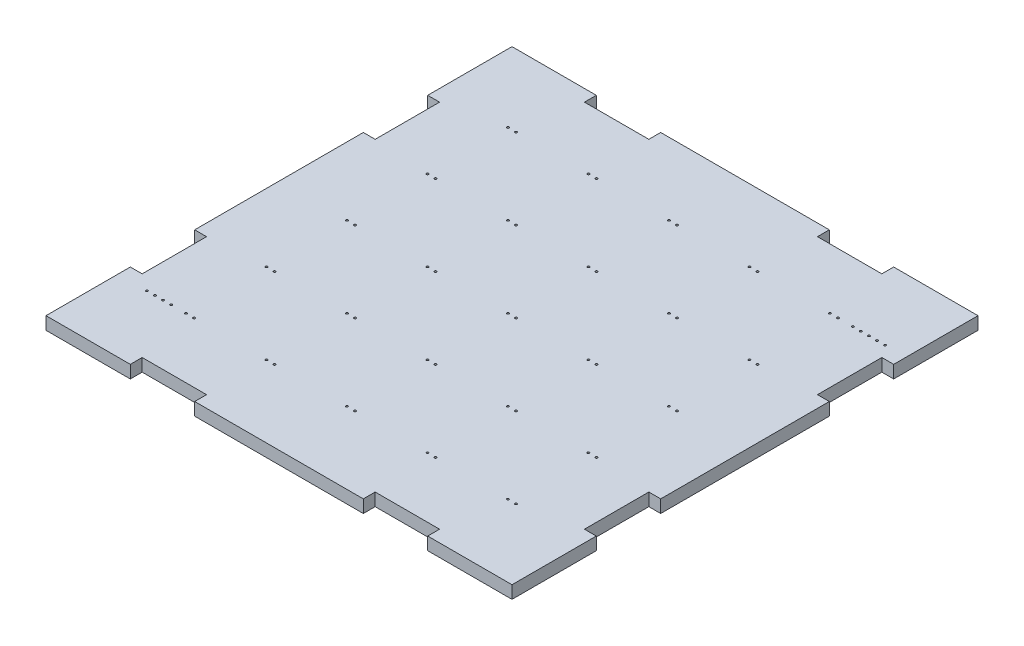
SolidWorks part; units mm, degrees
ref_plane "Front Plane" through (0, 0, 0) normal (0, 0, 1) x (1, 0, 0)
ref_plane "Top Plane" through (0, 0, 0) normal (0, 1, 0) x (1, 0, 0)
ref_plane "Right Plane" through (0, 0, 0) normal (1, 0, 0) x (0, 0, -1)
sketch "Sketch2" plane through (0, 0, 0) normal (0, 1, 0) x (1, 0, 0)
  line L1 (-110, -110) -> (110, -110)
  line L2 (-110, -110) -> (-110, 110)
  line L3 (-110, 110) -> (110, 110)
  line L4 (110, -110) -> (110, 110)
  line L5 (-110, -110) -> (110, 110) construction
  line L6 (-110, 110) -> (110, -110) construction
  point P0 (0, 0)
  dimension "D1" = 220
  dimension "D2" = 220
extrude "Boss-Extrude1" add sketch "Sketch2" along normal blind 6
sketch "Sketch3" plane through (0, 6, 0) normal (0, 1, 0) x (1, 0, 0)
  line L0 (-110, 110) -> (-110, -110) construction
  line L2 (-110, -110) -> (110, -110) construction
  circle A0 centre (-77.905, -76) radius 0.5
  circle A1 centre (-74.095, -76) radius 0.5
  circle A2 centre (-76, -76) radius 4 construction
  circle A3 centre (-38, -76) radius 4 construction
  circle A4 centre (-39.905, -76) radius 0.5
  circle A5 centre (-36.095, -76) radius 0.5
  circle A6 centre (0, -76) radius 4 construction
  circle A7 centre (-1.905, -76) radius 0.5
  circle A8 centre (1.905, -76) radius 0.5
  circle A9 centre (38, -76) radius 4 construction
  circle A10 centre (36.095, -76) radius 0.5
  circle A11 centre (39.905, -76) radius 0.5
  circle A12 centre (76, -76) radius 4 construction
  circle A13 centre (74.095, -76) radius 0.5
  circle A14 centre (77.905, -76) radius 0.5
  circle A15 centre (-38, -38) radius 4 construction
  circle A16 centre (-39.905, -38) radius 0.5
  circle A17 centre (-36.095, -38) radius 0.5
  circle A18 centre (0, -38) radius 4 construction
  circle A19 centre (-1.905, -38) radius 0.5
  circle A20 centre (1.905, -38) radius 0.5
  circle A21 centre (38, -38) radius 4 construction
  circle A22 centre (36.095, -38) radius 0.5
  circle A23 centre (39.905, -38) radius 0.5
  circle A24 centre (76, -38) radius 4 construction
  circle A25 centre (74.095, -38) radius 0.5
  circle A26 centre (77.905, -38) radius 0.5
  circle A27 centre (-38, 0) radius 4 construction
  circle A28 centre (-39.905, 0) radius 0.5
  circle A29 centre (-36.095, 0) radius 0.5
  circle A30 centre (0, 0) radius 4 construction
  circle A31 centre (-1.905, 0) radius 0.5
  circle A32 centre (1.905, 0) radius 0.5
  circle A33 centre (38, 0) radius 4 construction
  circle A34 centre (36.095, 0) radius 0.5
  circle A35 centre (39.905, 0) radius 0.5
  circle A36 centre (76, 0) radius 4 construction
  circle A37 centre (74.095, 0) radius 0.5
  circle A38 centre (77.905, 0) radius 0.5
  circle A39 centre (-38, 38) radius 4 construction
  circle A40 centre (-39.905, 38) radius 0.5
  circle A41 centre (-36.095, 38) radius 0.5
  circle A42 centre (0, 38) radius 4 construction
  circle A43 centre (-1.905, 38) radius 0.5
  circle A44 centre (1.905, 38) radius 0.5
  circle A45 centre (38, 38) radius 4 construction
  circle A46 centre (36.095, 38) radius 0.5
  circle A47 centre (39.905, 38) radius 0.5
  circle A48 centre (76, 38) radius 4 construction
  circle A49 centre (74.095, 38) radius 0.5
  circle A50 centre (77.905, 38) radius 0.5
  circle A51 centre (-38, 76) radius 4 construction
  circle A52 centre (-39.905, 76) radius 0.5
  circle A53 centre (-36.095, 76) radius 0.5
  circle A54 centre (0, 76) radius 4 construction
  circle A55 centre (-1.905, 76) radius 0.5
  circle A56 centre (1.905, 76) radius 0.5
  circle A57 centre (38, 76) radius 4 construction
  circle A58 centre (36.095, 76) radius 0.5
  circle A59 centre (39.905, 76) radius 0.5
  circle A60 centre (76, 76) radius 4 construction
  circle A61 centre (74.095, 76) radius 0.5
  circle A62 centre (77.905, 76) radius 0.5
  circle A63 centre (-76, -38) radius 4 construction
  circle A64 centre (-77.905, -38) radius 0.5
  circle A65 centre (-74.095, -38) radius 0.5
  circle A66 centre (-76, 0) radius 4 construction
  circle A67 centre (-77.905, 0) radius 0.5
  circle A68 centre (-74.095, 0) radius 0.5
  circle A69 centre (-76, 38) radius 4 construction
  circle A70 centre (-77.905, 38) radius 0.5
  circle A71 centre (-74.095, 38) radius 0.5
  circle A72 centre (-76, 76) radius 4 construction
  circle A73 centre (-77.905, 76) radius 0.5
  circle A74 centre (-74.095, 76) radius 0.5
  dimension "D1" = 1
  dimension "D2" = 1
  dimension "D4" = 8
  dimension "D7" = 30
  dimension "D10" = 30
  dimension "D11" = 30
  dimension "D3" = 1.905
  dimension "D5" = 1.905
  dimension "D6" = 30
  dimension "D8" = 5
  dimension "D9" = 5
extrude "Cut-Extrude1" cut sketch "Sketch3" against normal through all
sketch "Sketch4" plane through (0, 6, 0) normal (0, 1, 0) x (1, 0, 0)
  circle A0 centre (84.905, 76) radius 0.5
  circle A1 centre (88.715, 76) radius 0.5
  circle A2 centre (92.525, 76) radius 0.5
  circle A3 centre (96.335, 76) radius 0.5
  circle A4 centre (100.145, 76) radius 0.5
  circle A5 centre (-84.905, -76) radius 0.5
  circle A6 centre (-88.715, -76) radius 0.5
  circle A7 centre (-92.525, -76) radius 0.5
  circle A8 centre (-96.335, -76) radius 0.5
  point P3 (77.905, 76)
  point P4 (-77.905, -76)
  dimension "D1" = 1
  dimension "D5" = 1
  dimension "D7" = 4
  dimension "D2" = 7
  dimension "D4" = 3.81
  dimension "D6" = 7
  dimension "D8" = 3.81
  dimension "D3" = 5
extrude "Cut-Extrude2" cut sketch "Sketch4" against normal through all
sketch "Sketch5" plane through (0, 6, 0) normal (0, 1, 0) x (1, 0, 0)
  line L0 (110, 110) -> (-110, 110) construction
  line L1 (-70.2, 110) -> (-39.8, 110)
  line L2 (-70.2, 110) -> (-70.2, 104.4)
  line L3 (-70.2, 104.4) -> (-39.8, 104.4)
  line L4 (-39.8, 110) -> (-39.8, 104.4)
  line L5 (0, -3.3) -> (0, 3.3) construction
  line L6 (-104.4, -70.2) -> (-104.4, -39.8)
  line L7 (70.2, 110) -> (39.8, 110)
  line L8 (39.8, 110) -> (39.8, 104.4)
  line L9 (70.2, 104.4) -> (39.8, 104.4)
  line L10 (70.2, 110) -> (70.2, 104.4)
  line L11 (-3.3, 0) -> (3.3, 0) construction
  line L12 (70.2, -110) -> (70.2, -104.4)
  line L13 (70.2, -104.4) -> (39.8, -104.4)
  line L14 (39.8, -110) -> (39.8, -104.4)
  line L15 (70.2, -110) -> (39.8, -110)
  line L16 (-39.8, -110) -> (-39.8, -104.4)
  line L17 (-70.2, -104.4) -> (-39.8, -104.4)
  line L18 (-70.2, -110) -> (-70.2, -104.4)
  line L19 (-70.2, -110) -> (-39.8, -110)
  line L20 (-110, 110) -> (-110, -110) construction
  line L21 (-110, 70.2) -> (-104.4, 70.2)
  line L22 (-110, 70.2) -> (-110, 39.8)
  line L23 (-110, 39.8) -> (-104.4, 39.8)
  line L24 (-104.4, 70.2) -> (-104.4, 39.8)
  line L25 (-110, -39.8) -> (-104.4, -39.8)
  line L26 (-110, -70.2) -> (-110, -39.8)
  line L27 (-110, -70.2) -> (-104.4, -70.2)
  line L28 (110, -70.2) -> (104.4, -70.2)
  line L29 (110, -70.2) -> (110, -39.8)
  line L30 (110, -39.8) -> (104.4, -39.8)
  line L31 (104.4, 70.2) -> (104.4, 39.8)
  line L32 (110, 39.8) -> (104.4, 39.8)
  line L33 (110, 70.2) -> (110, 39.8)
  line L34 (110, 70.2) -> (104.4, 70.2)
  line L35 (104.4, -70.2) -> (104.4, -39.8)
  dimension "D1" = 5.6
  dimension "D2" = 30.4
  dimension "D3" = 39.8
  dimension "D4" = 30.4
  dimension "D5" = 5.6
  dimension "D6" = 39.8
extrude "Cut-Extrude3" cut sketch "Sketch5" against normal through all
